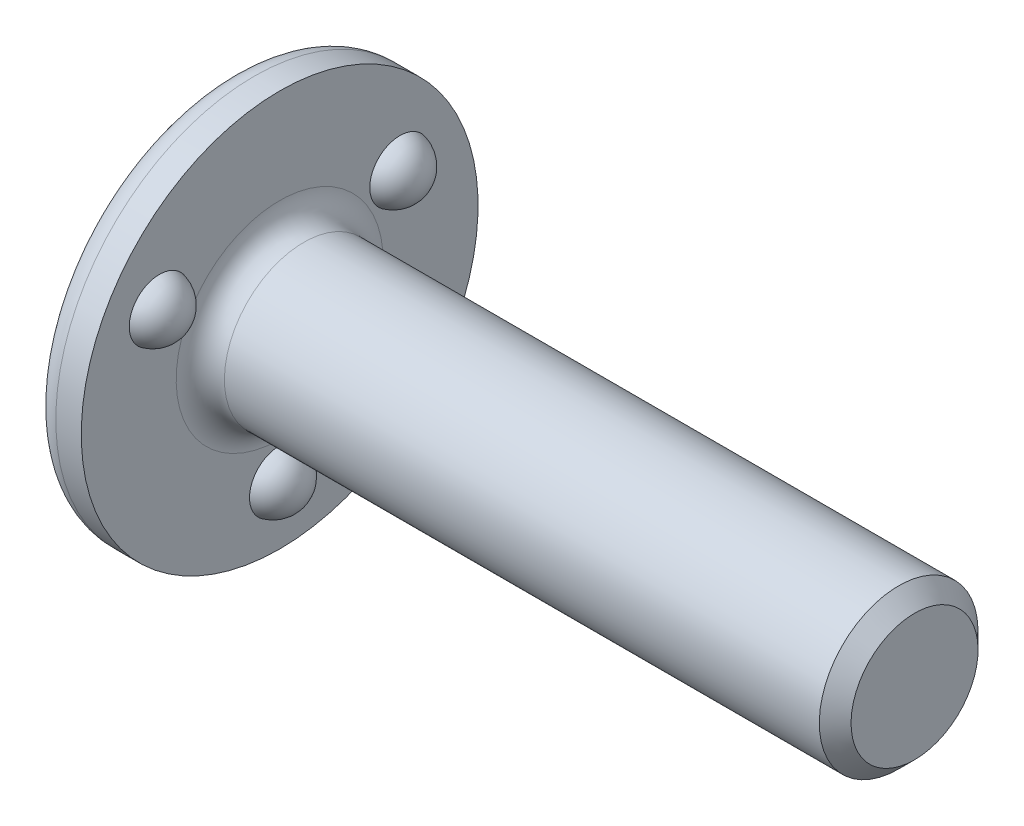
SolidWorks part; units mm, degrees
material "1023 Carbon Steel Sheet (SS)"
ref_plane "Front" through (0, 0, 0) normal (0, 0, 1) x (1, 0, 0)
ref_plane "Top" through (0, 0, 0) normal (0, 1, 0) x (1, 0, 0)
ref_plane "Right" through (0, 0, 0) normal (1, 0, 0) x (0, 0, -1)
sketch "Sketch1" plane through (0, 0, 0) normal (0, 0, 1) x (1, 0, 0)
  line L0 (0, 0) -> (0, 7.9375)
  line L1 (0, 7.9375) -> (1.9844, 7.9375)
  line L2 (1.9844, 7.9375) -> (1.9844, 3.175)
  line L3 (1.9844, 3.175) -> (27.3844, 3.175)
  line L4 (27.3844, 3.175) -> (27.3844, 0)
  line L5 (0, 0) -> (27.3844, 0) construction
  line L6 (0, 0) -> (27.3844, 0)
  dimension "Base Diameter" = 15.875
  dimension "Shaft Diameter" = 6.35
  dimension "Base Thickness" = 1.9844
  dimension "Shaft Length" = 25.4
revolve "Revolve1" add sketch "Sketch1" angle 360 about L5
chamfer "Chamfer1" distance 0.635 angle 45 1 edges at (27.3844, -3.175, 0)
sketch "Sketch4" plane through (0, 0, 0) normal (0, 0, 1) x (1, 0, 0)
  line L0 (1.9844, -3.175) -> (1.9844, -7.9375) construction
  line L1 (1.9844, -3.175) -> (1.9844, 3.175) construction
  line L2 (1.9844, -7.9375) -> (1.9844, 7.9375) construction
  line L3 (1.9844, -5.5563) -> (0, -5.5563) construction
  line L4 (0, 7.9375) -> (0, -7.9375) construction
  line L5 (1.9844, -5.5563) -> (1.9844, -4.3498)
  line L6 (1.9844, -5.5563) -> (2.9496, -5.5563)
  line L7 (0.9922, -5.5563) -> (0.9922, 7.9375) construction
  line L8 (1.9844, 7.9375) -> (0, 7.9375) construction
  line L9 (2.9496, -5.5563) -> (2.9496, -4.3498) construction
  line L10 (0, -5.5563) -> (-0.9652, -5.5563)
  line L11 (0, -5.5563) -> (0, -4.3498)
  arc A0 (2.9496, -5.5563) -> (1.9844, -4.3498) centre (1.7129, -5.5563) ccw
  arc A1 (-0.9652, -5.5563) -> (0, -4.3498) centre (0.2715, -5.5563) cw
  dimension "P" = 2.413
  dimension "F" = 0.9652
sketch "Sketch3" [suppressed] plane through (0, 0, 0) normal (0, 0, 1) x (1, 0, 0)
  line L0 (1.1906, 3.175) -> (1.1906, 1.5875) construction
  line L2 (1.1906, -1.5875) -> (1.1906, 1.5875) construction
  line L5 (1.1906, 2.3812) -> (0, 2.3812) construction
  line L6 (0, 3.175) -> (0, -3.175) construction
  line L7 (0, 2.3812) -> (-0.4572, 2.3812)
  line L8 (0, 2.3812) -> (0, 2.9527)
  line L9 (-0.4572, 2.3812) -> (-0.4572, 2.9527) construction
  arc A0 (-0.4572, 2.3812) -> (0, 2.9527) centre (0.1286, 2.3812) cw
  arc A1 (0, 2.9527) -> (-0.4572, 2.3812) centre (0.1286, 2.3812) ccw construction
revolve "Revolve3" [suppressed] add sketch "Sketch3" angle 360 about L5
pattern_circular "CirPattern2" [suppressed] count 3 over 360
fillet "Fillet2" [suppressed] radius 0.9652
sketch "Sketch2" plane through (0, 0, 0) normal (0, 0, 1) x (1, 0, 0)
  line L0 (1.9844, -7.9375) -> (1.9844, -3.175) construction
  line L1 (1.9844, -3.175) -> (1.9844, 3.175) construction
  line L2 (1.9844, -7.9375) -> (1.9844, 7.9375) construction
  line L3 (1.9844, -5.5563) -> (2.9496, -5.5563)
  line L4 (1.9844, -5.5563) -> (1.9844, -4.3498)
  line L5 (1.9844, -5.5563) -> (0, -5.5563) construction
  line L6 (0, 7.9375) -> (0, -7.9375) construction
  line L7 (2.9496, -5.5563) -> (2.9496, -4.3498) construction
  arc A0 (2.9496, -5.5563) -> (1.9844, -4.3498) centre (1.7129, -5.5563) ccw
  point P8 (1.9844, -5.5563)
revolve "Revolve2" add sketch "Sketch2" angle 360 about L5
pattern_circular "CirPattern1" count 3 over 360 about axis through (0, 0, 0) along (1, 0, 0) of "Revolve2"
fillet "Fillet1" radius 0.9652 2 edges at (0, -7.9375, 0) (1.9844, -3.175, 0)
equation "\"D1@Chamfer1\" = \"Shaft Diameter@Sketch1\"*.1"
equation "\"D1@Fillet1\" = \"F@Sketch4\""
equation "\"D1@Fillet2\" = \"F@Sketch4\""
